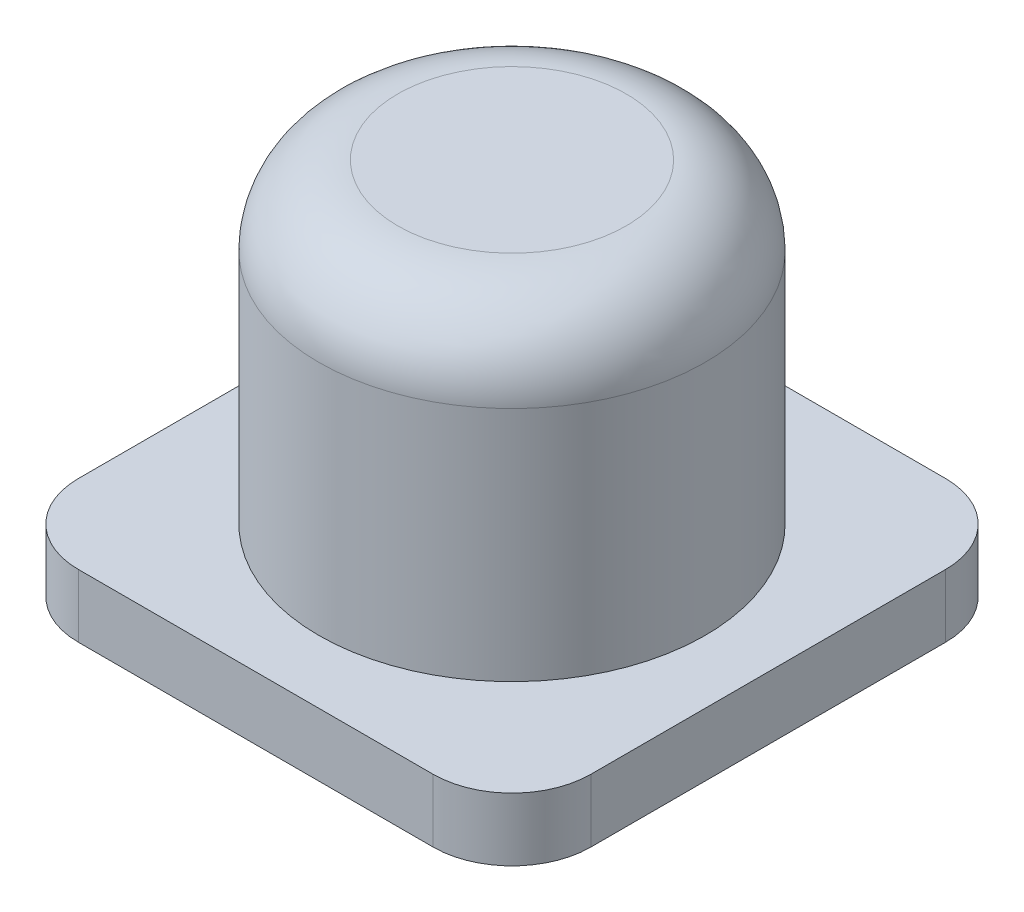
SolidWorks part; units mm, degrees
ref_plane "Front Plane" through (0, 0, 0) normal (0, 0, 1) x (1, 0, 0)
ref_plane "Top Plane" through (0, 0, 0) normal (0, 1, 0) x (1, 0, 0)
ref_plane "Right Plane" through (0, 0, 0) normal (1, 0, 0) x (0, 0, -1)
sketch "Sketch1" plane through (0, 0, 0) normal (0, 1, 0) x (1, 0, 0)
  line L1 (-1.625, 1.625) -> (1.625, 1.625)
  line L2 (-1.625, 1.625) -> (-1.625, -1.625)
  line L3 (-1.625, -1.625) -> (1.625, -1.625)
  line L4 (1.625, 1.625) -> (1.625, -1.625)
  line L5 (-1.625, 1.625) -> (1.625, -1.625) construction
  line L6 (-1.625, -1.625) -> (1.625, 1.625) construction
  point P0 (0, 0)
  dimension "D1" = 3.25
  dimension "D2" = 3.25
extrude "Boss-Extrude1" add sketch "Sketch1" along normal blind 0.4
sketch "Sketch2" plane through (0, 0.4, 0) normal (0, 1, 0) x (1, 0, 0)
  circle A0 centre (0, 0) radius 1.225
  dimension "D1" = 2.45
extrude "Boss-Extrude2" add sketch "Sketch2" along normal blind 2
fillet "Fillet1" radius 0.5 1 edges at (0, 2.4, 1.225)
fillet "Fillet2" radius 0.5 4 edges at (-1.625, 0.2, 1.625) (-1.625, 0.2, -1.625) (1.625, 0.2, -1.625) (1.625, 0.2, 1.625)
